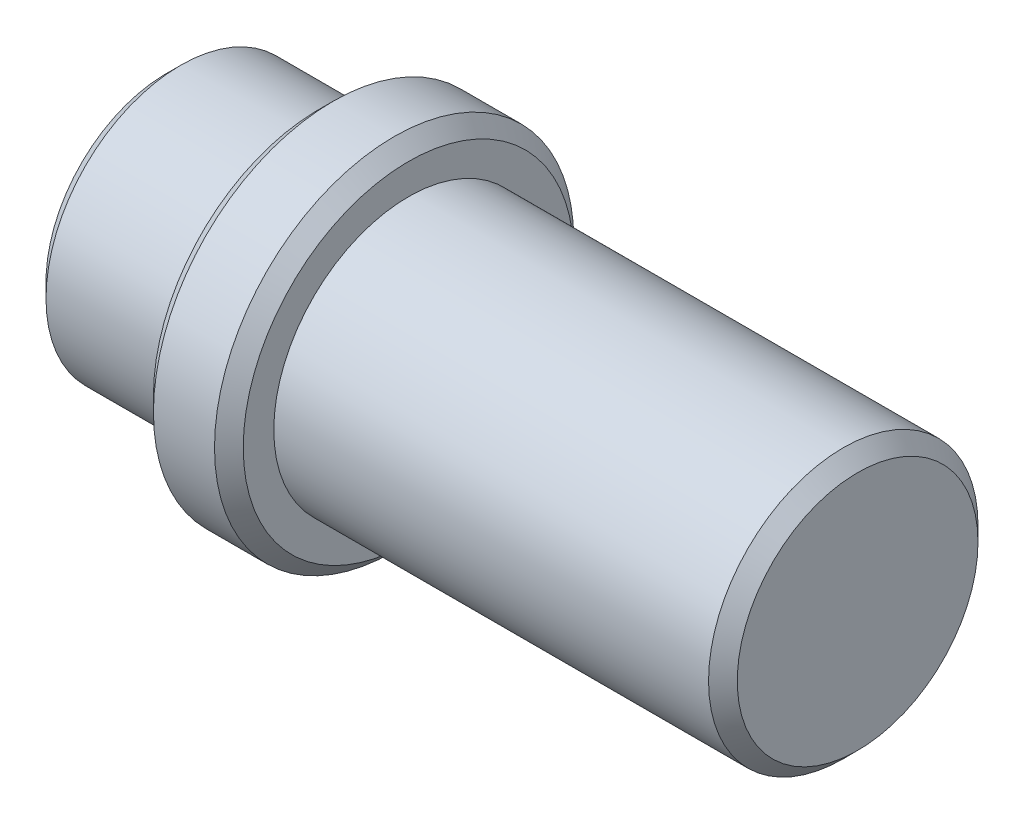
SolidWorks part; units mm, degrees
material "AISI 316 Stainless Steel Sheet (SS)"
ref_plane "Front Plane" through (0, 0, 0) normal (0, 0, 1) x (1, 0, 0)
ref_plane "Top Plane" through (0, 0, 0) normal (0, 1, 0) x (1, 0, 0)
ref_plane "Right Plane" through (0, 0, 0) normal (1, 0, 0) x (0, 0, -1)
sketch "Sketch1" plane through (0, 0, 0) normal (1, 0, 0) x (0, 0, -1)
  circle A0 centre (0, 0) radius 2.3813
  dimension "D1" = 4.7625
extrude "Boss-Extrude1" add sketch "Sketch1" along normal blind 12.2174
ref_plane "Plane1" through (2.6924, 0, 0) normal (-1, 0, 0) x (0, 0, 1)
sketch "Sketch2" plane through (2.6924, 0, 0) normal (-1, 0, 0) x (0, 0, 1)
  circle A0 centre (0, 0) radius 3.175
  dimension "D1" = 6.35
extrude "Boss-Extrude2" add sketch "Sketch2" against normal blind 1.5875
chamfer "Chamfer1" distance 0.254 angle 45 4 edges at (0, 0, -2.3813) (12.2174, 0, -2.3813) (4.2799, 0, 3.175) (2.6924, 0, 3.175)
